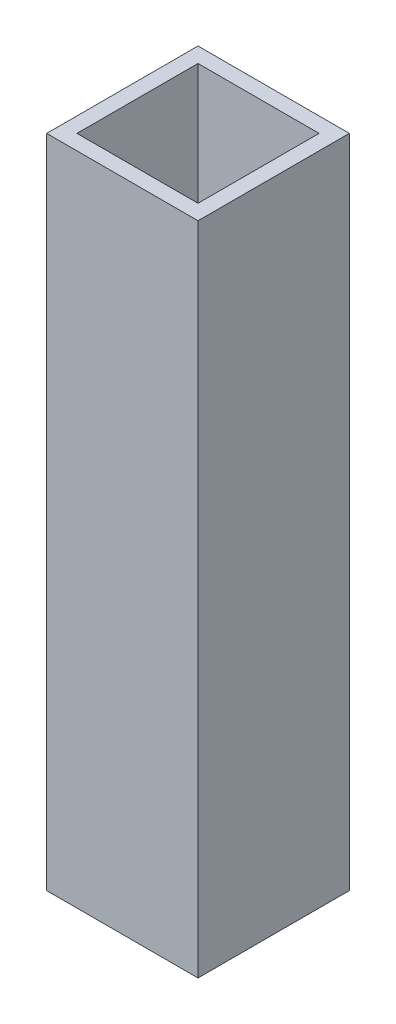
SolidWorks part; units mm, degrees
ref_plane "Alzado" through (0, 0, 0) normal (0, 0, 1) x (1, 0, 0)
ref_plane "Planta" through (0, 0, 0) normal (0, 1, 0) x (1, 0, 0)
ref_plane "Vista lateral" through (0, 0, 0) normal (1, 0, 0) x (0, 0, -1)
sketch "Croquis1" plane through (0, 0, 0) normal (0, 1, 0) x (1, 0, 0)
  line L1 (-15, 15) -> (15, 15)
  line L2 (-15, 15) -> (-15, -15)
  line L3 (-15, -15) -> (15, -15)
  line L4 (15, 15) -> (15, -15)
  line L5 (-15, 15) -> (15, -15) construction
  line L6 (-15, -15) -> (15, 15) construction
  line L7 (-12, 12) -> (12, 12)
  line L8 (-12, 12) -> (-12, -12)
  line L9 (-12, -12) -> (12, -12)
  line L10 (12, 12) -> (12, -12)
  line L11 (-12, 12) -> (12, -12) construction
  line L12 (-12, -12) -> (12, 12) construction
  point P0 (0, 0)
  point P6 (0, 0)
  dimension "D1" = 30
  dimension "D2" = 3
  dimension "D3" = 30
extrude "Saliente-Extruir1" add sketch "Croquis1" along normal blind 130
